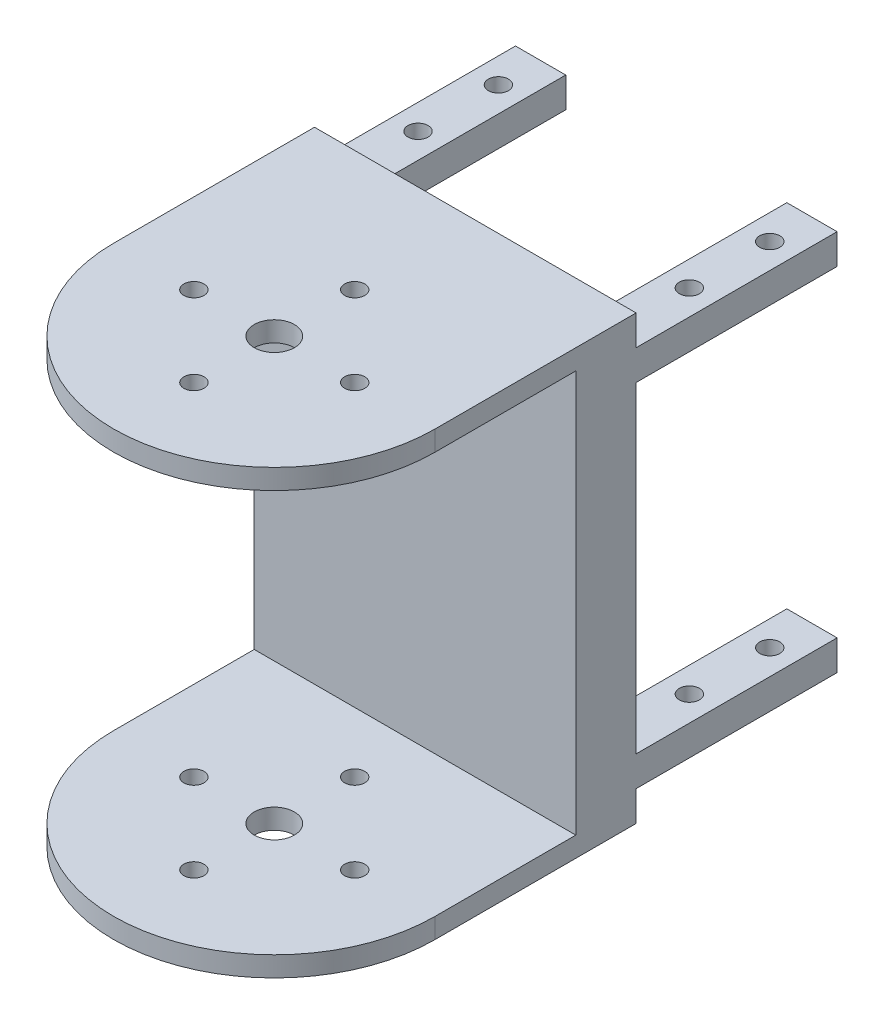
SolidWorks part; units mm, degrees
ref_plane "Front Plane" through (0, 0, 0) normal (0, 0, 1) x (1, 0, 0)
ref_plane "Top Plane" through (0, 0, 0) normal (0, 1, 0) x (1, 0, 0)
ref_plane "Right Plane" through (0, 0, 0) normal (1, 0, 0) x (0, 0, -1)
sketch "Sketch1" plane through (0, 0, 0) normal (0, 1, 0) x (1, 0, 0)
  line L0 (0, 0) -> (0, 8) construction
  line L1 (-16, 0) -> (-16, 20)
  line L2 (-16, 20) -> (16, 20)
  line L3 (16, 20) -> (16, 0)
  arc A0 (-16, 0) -> (16, 0) centre (0, 0) ccw
  circle A1 centre (0, 8) radius 1
  circle A2 centre (8, 0) radius 1
  circle A3 centre (0, -8) radius 1
  circle A4 centre (-8, 0) radius 1
  circle A5 centre (0, 0) radius 2
  dimension "D1" = 32
  dimension "D2" = 2
  dimension "D6" = 4
  dimension "D3" = 8
  dimension "D5" = 20
  dimension "D4" = 4
extrude "Boss-Extrude1" add sketch "Sketch1" along normal blind 44
sketch "Sketch2" plane through (16, 0, 0) normal (1, 0, 0) x (0, 0, -1)
  line L1 (-16, 42) -> (14, 42)
  line L2 (-16, 42) -> (-16, 2)
  line L3 (-16, 2) -> (14, 2)
  line L4 (14, 42) -> (14, 2)
  line L5 (-16, 42) -> (14, 2) construction
  line L6 (-16, 2) -> (14, 42) construction
  line L7 (0, 0) -> (20, 0) construction
  line L8 (-16, 44) -> (-16, 0) construction
  point P0 (-1, 22)
  point P7 (3.5, 23.8385)
  point P8 (0, 0)
  dimension "D1" = 30
  dimension "D2" = 22
  dimension "D3" = 40
extrude "Cut-Extrude1" cut sketch "Sketch2" against normal through all
sketch "Sketch3" plane through (0, 0, -20) normal (0, 0, -1) x (-1, 0, 0)
  line L0 (-16, 0) -> (16, 0) construction
  line L1 (-16, 38) -> (16, 38) construction
  line L2 (-16, 38) -> (-16, 6) construction
  line L3 (-16, 6) -> (16, 6) construction
  line L4 (16, 38) -> (16, 6) construction
  line L5 (-16, 38) -> (16, 6) construction
  line L6 (-16, 6) -> (16, 38) construction
  line L8 (-16, 38) -> (-11, 38)
  line L9 (-16, 38) -> (-16, 41)
  line L10 (-16, 41) -> (-11, 41)
  line L11 (-11, 38) -> (-11, 41)
  line L12 (16, 38) -> (11, 38)
  line L13 (16, 38) -> (16, 41)
  line L14 (16, 41) -> (11, 41)
  line L15 (11, 38) -> (11, 41)
  line L16 (-16, 6) -> (-11, 6)
  line L17 (-16, 6) -> (-16, 3)
  line L18 (-16, 3) -> (-11, 3)
  line L19 (-11, 6) -> (-11, 3)
  line L20 (16, 6) -> (11, 6)
  line L21 (16, 6) -> (16, 3)
  line L22 (16, 3) -> (11, 3)
  line L23 (11, 6) -> (11, 3)
  point P0 (0, 22)
  dimension "D1" = 22
  dimension "D2" = 38
  dimension "D3" = 22
  dimension "D4" = 3
  dimension "D5" = 5
extrude "Boss-Extrude2" add sketch "Sketch3" along normal blind 20
sketch "Sketch4" plane through (0, 0, 0) normal (0, -1, 0) x (1, 0, 0)
  line L0 (16, -20) -> (-16, -20) construction
  line L1 (-16, -40) -> (-16, -20) construction
  line L2 (11, -40) -> (11, -20) construction
  circle A0 centre (-13.5, -27.8) radius 1
  circle A1 centre (-13.5, -35.8) radius 1
  circle A2 centre (13.5, -27.8) radius 1
  circle A3 centre (13.5, -35.8) radius 1
  point P8 (0, 0)
  point P11 (-8.7419, -32.689)
  point P14 (0, 0)
  point P15 (8.7532, -36.4789)
  point P16 (0, 0)
  dimension "D1" = 2
  dimension "D4" = 2.5
  dimension "D2" = 7.8
  dimension "D3" = 8
  dimension "D5" = 2.5
extrude "Cut-Extrude2" cut sketch "Sketch4" against normal through all
